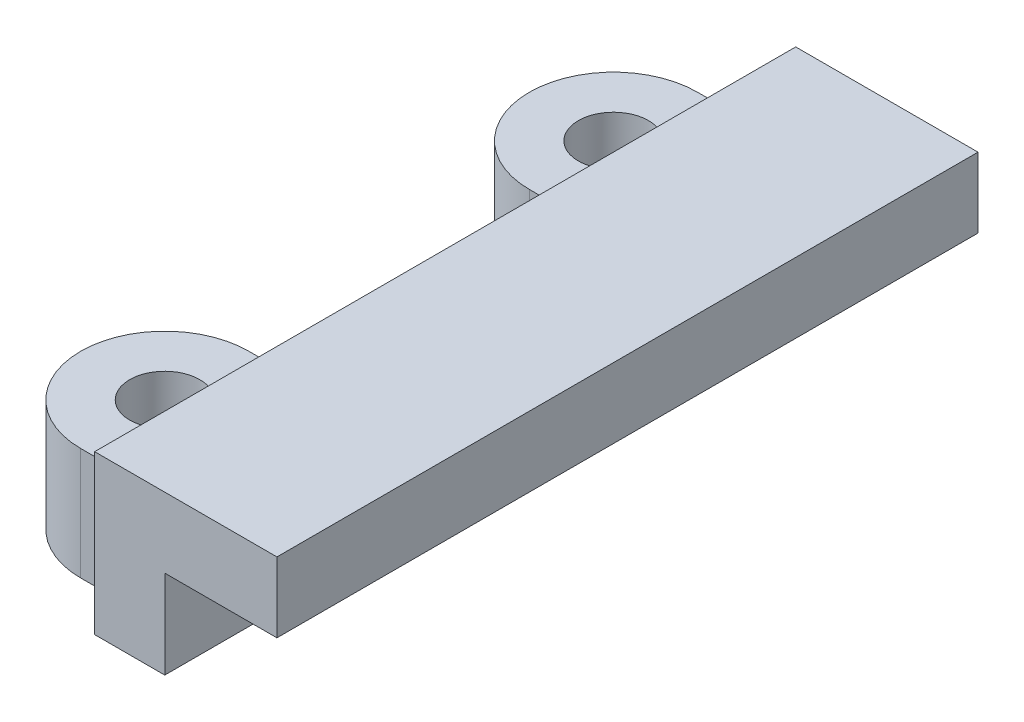
SolidWorks part; units mm, degrees
ref_plane "Alzado" through (0, 0, 0) normal (0, 0, 1) x (1, 0, 0)
ref_plane "Planta" through (0, 0, 0) normal (0, 1, 0) x (1, 0, 0)
ref_plane "Vista lateral" through (0, 0, 0) normal (1, 0, 0) x (0, 0, -1)
sketch "Croquis1" plane through (0, 0, 0) normal (0, 0, 1) x (1, 0, 0)
  line L0 (0, 0) -> (0, 11.3)
  line L1 (0, 11.3) -> (13, 11.3)
  line L2 (13, 11.3) -> (13, 6.3)
  line L3 (13, 6.3) -> (5, 6.3)
  line L4 (5, 6.3) -> (5, 0)
  line L5 (5, 0) -> (0, 0)
  dimension "D1" = 6.3
  dimension "D2" = 5
  dimension "D3" = 8
  dimension "D4" = 5
sketch "Croquis3" plane through (0, 0, 0) normal (0, 1, 0) x (1, 0, 0)
  line L0 (0, 0) -> (0, -37)
  dimension "D1" = 37
sweep "Barrer1" add profiles "Croquis1" path "Croquis3"
ref_plane "Plano1" through (80.5, 0, 0) normal (-1, 0, 0) x (0, 0, 1)
sketch "Croquis4" plane through (0, 0, 0) normal (-1, 0, 0) x (0, 0, 1)
  line L0 (0, 0) -> (37, 0) construction
  line L1 (37, 11.3) -> (50, 11.3)
  line L2 (37, 11.3) -> (37, 0)
  line L3 (37, 0) -> (50, 0)
  line L4 (50, 11.3) -> (50, 0)
  dimension "D1" = 13
extrude "Saliente-Extruir1" add sketch "Croquis4" against normal blind 161
mirror "Simetría5" about plane through (80.5, 0, 0) normal (-1, 0, 0) of "Barrer1"
sketch "Croquis5" plane through (0, 0, 0) normal (0, -1, 0) x (1, 0, 0)
  line L1 (5, 37) -> (156, 37)
  line L2 (5, 37) -> (5, 40.5)
  line L3 (5, 40.5) -> (156, 40.5)
  line L4 (156, 37) -> (156, 40.5)
  dimension "D1" = 3.5
  dimension "D2" = 151
extrude "Cortar-Extruir1" cut sketch "Croquis5" against normal blind 6.3
sketch "Croquis6" plane through (0, 0, 50) normal (0, 0, 1) x (1, 0, 0)
  line L0 (161, 11.3) -> (0, 11.3) construction
  line L1 (16, 11.3) -> (26, 11.3)
  line L2 (16, 11.3) -> (16, 14)
  line L4 (26, 11.3) -> (26, 14)
  line L5 (0, 0) -> (0, 11.3) construction
  arc A0 (26, 14) -> (16, 14) centre (21, 14) ccw
  dimension "D1" = 2.7
  dimension "D2" = 10
  dimension "D3" = 21
extrude "Saliente-Extruir2" [suppressed] add sketch "Croquis6" against normal blind 10
sketch "Croquis7" [suppressed] plane through (0, 0, 50) normal (0, 0, 1) x (1, 0, 0)
  circle A0 centre (21, 14) radius 3
  dimension "D1" = 6
extrude "Cortar-Extruir2" [suppressed] cut sketch "Croquis7" against normal through all
mirror "Simetría6" [suppressed] about plane through (80.5, 0, 0) normal (-1, 0, 0)
sketch "Croquis8" plane through (0, 0, 0) normal (0, -1, 0) x (1, 0, 0)
  line L0 (161, 0) -> (161, 50) construction
  line L1 (161, 47) -> (165, 47)
  line L2 (161, 47) -> (161, 35)
  line L3 (161, 35) -> (165, 35)
  line L5 (161, 50) -> (0, 50) construction
  arc A0 (165, 35) -> (165, 47) centre (165, 41) ccw
  dimension "D1" = 4
  dimension "D2" = 12
  dimension "D3" = 9
extrude "Saliente-Extruir3" add sketch "Croquis8" against normal blind 8
sketch "Croquis9" plane through (0, 0, 0) normal (0, -1, 0) x (1, 0, 0)
  circle A0 centre (165, 41) radius 2.5
  dimension "D1" = 5
extrude "Cortar-Extruir3" cut sketch "Croquis9" against normal through all
ref_plane "Plano2" through (0, 0, 25) normal (0, 0, -1) x (-1, 0, 0)
mirror "Simetría7" about plane through (0, 0, 25) normal (0, 0, -1) of "Saliente-Extruir3", "Cortar-Extruir3"
mirror "Simetría8" about plane through (80.5, 0, 0) normal (-1, 0, 0) of "Simetría7", "Saliente-Extruir3", "Cortar-Extruir3"
sketch "Croquis10" plane through (0, 11.3, 0) normal (0, 1, 0) x (1, 0, 0)
  line L0 (161, -50) -> (161, 0) construction
  line L1 (161, -50) -> (0, -50) construction
  circle A0 centre (121, -45.25) radius 2.5
  dimension "D3" = 5
  dimension "D1" = 40
  dimension "D2" = 4.75
extrude "Cortar-Extruir4" cut sketch "Croquis10" against normal through all
pattern_linear "MatrizL1" count 3 spacing 40.5 along (-1, 0, 0) of "Cortar-Extruir4"
ref_plane "Plano3" through (13, 0, 0) normal (1, 0, 0) x (0, 0, -1)
sketch "Croquis11" plane through (13, 0, 0) normal (1, 0, 0) x (0, 0, -1)
  line L1 (-59.3834, 19.3777) -> (5.4703, 19.3777)
  line L2 (-59.3834, 19.3777) -> (-59.3834, -3.5873)
  line L3 (-59.3834, -3.5873) -> (5.4703, -3.5873)
  line L4 (5.4703, 19.3777) -> (5.4703, -3.5873)
extrude "Cortar-Extruir5" cut sketch "Croquis11" along normal through all
sketch "Croquis12" plane through (0, 0, 40.5) normal (0, 0, -1) x (-1, 0, 0)
  line L4 (-13, 6.3) -> (-13, 0)
  line L5 (-13, 0) -> (-5, 0)
  line L6 (-5, 0) -> (-5, 6.3)
  line L7 (-5, 6.3) -> (-13, 6.3)
  line L8 (-13, 6.3) -> (-13, 0)
  line L9 (-13, 0) -> (-5, 0)
  line L10 (-5, 0) -> (-5, 6.3)
  line L11 (-5, 6.3) -> (-13, 6.3)
  dimension "D1" = 0
extrude "Cortar-Extruir6" cut sketch "Croquis12" against normal through all
ref_plane "Plano4" through (0, 0, 25) normal (0, 0, -1) x (-1, 0, 0)
